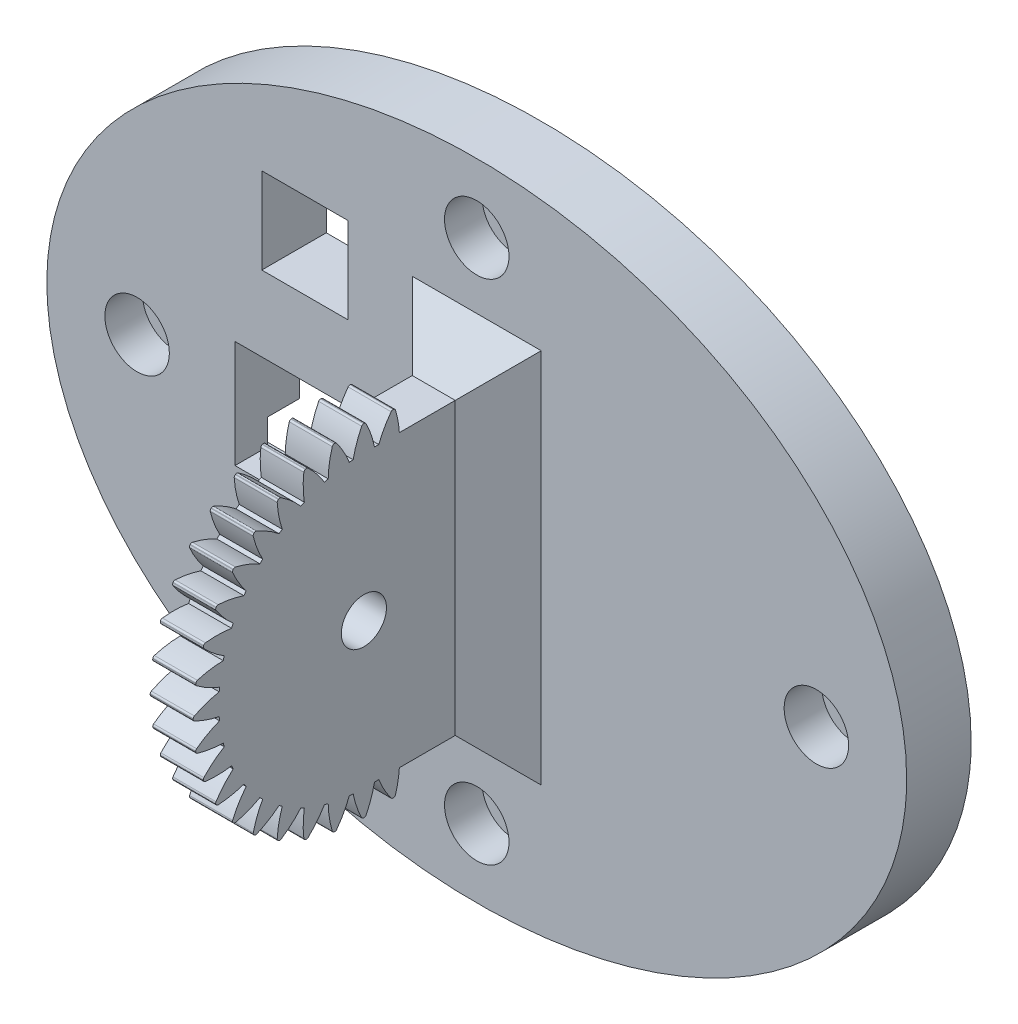
SolidWorks part; units mm, degrees
material "PET"
ref_plane "Front Plane" through (0, 0, 0) normal (0, 0, 1) x (1, 0, 0)
ref_plane "Top Plane" through (0, 0, 0) normal (0, 1, 0) x (1, 0, 0)
ref_plane "Right Plane" through (0, 0, 0) normal (1, 0, 0) x (0, 0, -1)
sketch "Sketch2" plane through (0, 0, 0) normal (0, 0, 1) x (1, 0, 0)
  ellipse E0 centre (0, 0) end of major axis (50.8, 0) minor radius 38.1
  dimension "D1" = 101.6
  dimension "D2" = 76.2
extrude "Boss-Extrude1" add sketch "Sketch2" along normal blind 7.62
ref_plane "Plane1" through (0, 0, 12.7) normal (0, 0, 1) x (1, 0, 0)
sketch "Sketch6" plane through (0, 0, 7.62) normal (0, 0, 1) x (1, 0, 0)
  line L0 (0, 38.1) -> (0, 29.972) construction
  circle A0 centre (0, 29.972) radius 2.2225
  ellipse E0 centre (0, 0) end of major axis (50.8, 0) minor radius 38.1 construction
  ellipse E1 centre (0, 0) end of major axis (50.8, 0) minor radius 38.1
  dimension "D2" = 4.445
  dimension "D1" = 8.128
extrude "Cut-Extrude1" cut sketch "Sketch6" against normal through all
sketch "Sketch7" plane through (0, 0, 7.62) normal (0, 0, 1) x (1, 0, 0)
  circle A0 centre (0, 29.972) radius 3.81
  dimension "D1" = 7.62
extrude "Cut-Extrude2" cut sketch "Sketch7" against normal blind 4.445
mirror "Mirror1" about plane through (0, 0, 0) normal (0, 1, 0) of "Cut-Extrude2", "Cut-Extrude1"
sketch "Sketch8" plane through (0, 0, 7.62) normal (0, 0, 1) x (1, 0, 0)
  line L0 (-50.8, 0) -> (-40.132, 0) construction
  circle A0 centre (-40.132, 0) radius 2.2225
  ellipse E0 centre (0, 0) end of major axis (50.8, 0) minor radius 38.1 construction
  dimension "D2" = 4.445
  dimension "D1" = 10.668
extrude "Cut-Extrude3" cut sketch "Sketch8" against normal through all
sketch "Sketch9" plane through (0, 0, 7.62) normal (0, 0, 1) x (1, 0, 0)
  circle A0 centre (-40.132, 0) radius 3.81
  dimension "D1" = 7.62
extrude "Cut-Extrude4" cut sketch "Sketch9" against normal blind 4.445
mirror "Mirror2" about plane through (0, 0, 0) normal (1, 0, 0) of "Cut-Extrude4", "Cut-Extrude3"
sketch "Sketch10" plane through (0, 0, 7.62) normal (0, 0, 1) x (1, 0, 0)
  line L0 (-36.322, 0) -> (36.322, 0)
  line L2 (-2.54, 17.145) -> (2.54, 17.145)
  line L3 (-2.54, 17.145) -> (-2.54, -17.145)
  line L4 (-2.54, -17.145) -> (2.54, -17.145)
  line L5 (2.54, 17.145) -> (2.54, -17.145)
  line L6 (-2.54, 17.145) -> (2.54, -17.145) construction
  line L7 (-2.54, -17.145) -> (2.54, 17.145) construction
  circle A0 centre (40.132, 0) radius 3.81 construction
  point P4 (0, 0)
  point P12 (0, 0)
  dimension "D1" = 5.08
  dimension "D3" = 34.29
extrude "Boss-Extrude2" add sketch "Sketch10" along normal blind 15.875
chamfer "Chamfer1" distance 5.08 angle 45 4 edges at (2.54, 0, 7.62) (-2.54, 0, 7.62) (0, -17.145, 7.62) (0, 17.145, 7.62)
sketch "Sketch11" plane through (-2.54, 0, 0) normal (-1, 0, 0) x (0, 0, 1)
  line L0 (23.495, 17.145) -> (23.495, -17.145) construction
  circle A0 centre (23.495, 0) radius 2.667
  point P0 (40.005, 0)
  point P6 (0, 0)
  point P7 (37.361, 0)
  dimension "D2" = 5.334
extrude "Cut-Extrude5" cut sketch "Sketch11" against normal through all
sketch "Sketch14" plane through (-2.54, 0, 0) normal (-1, 0, 0) x (0, 0, 1)
  circle A0 centre (23.495, 0) radius 17.145
  circle A1 centre (23.495, 0) radius 2.667
  circle A2 centre (23.495, 0) radius 2.667 construction
  dimension "D1" = 34.29
extrude "Boss-Extrude3" add sketch "Sketch14" against normal up to surface (5.08 mm away) up to face at (2.54, 0, 19.4522)
sketch "Sketch13" plane through (-2.54, 0, 0) normal (-1, 0, 0) x (0, 0, 1)
  line L0 (24.13, 0) -> (33.02, 0) construction
  line L2 (43.6626, 0.0351) -> (43.6626, -0.0351)
  arc A2 (40.5674, 1.27) -> (43.5227, 0.262) centre (38.3898, -9.9507) cw
  arc A3 (40.5674, -1.27) -> (43.5227, -0.262) centre (38.3898, 9.9507) ccw
  arc A6 (23.495, -17.1196) -> (23.495, 17.1196) centre (23.495, 0) ccw
  arc A7 (40.5674, -1.27) -> (40.5674, 1.27) centre (23.495, 0) ccw
  arc A8 (43.5227, -0.262) -> (43.6626, -0.0351) centre (43.4086, -0.0351) ccw
  arc A9 (43.6626, 0.0351) -> (43.5227, 0.262) centre (43.4086, 0.0351) ccw
  point P2 (60.1726, 0.3175)
  point P4 (43.6626, -0.1905)
  point P5 (60.1726, -0.3128)
  point P8 (60.1726, 0.3175)
  point P10 (40.6146, 0)
  point P12 (43.6626, 0.1905)
  point P18 (60.1726, -0.3175)
  point P19 (43.6626, 0)
  point P21 (60.1726, 0.3128)
  point P23 (43.6626, -0.1905)
  point P26 (43.6626, 0.1905)
  dimension "D1" = 0.0254
  dimension "D2" = 11.43
  dimension "D6" = 0.254
  dimension "D3" = 3.048
  dimension "D4" = 1.27
  dimension "D5" = 0.1905
extrude "Boss-Extrude4" add sketch "Sketch13" against normal up to surface (5.08 mm away) up to face at (2.54, 0, 22.3837)
pattern_circular "CirPattern1" count 36 over 360 about axis through (0, 0, 23.495) along (1, 0, 0) of "Boss-Extrude4"
sketch "Sketch16" plane through (0, 0, 7.62) normal (0, 0, 1) x (1, 0, 0)
  line L0 (-50.8, 0) -> (50.8, 0) construction
  line L1 (-50.7718, -1.27) -> (50.7718, -1.27) construction
  line L2 (0, 38.1) -> (0, -38.1) construction
  line L3 (-21.8948, 5.08) -> (-21.8948, -7.62) construction
  line L4 (-28.5623, 5.08) -> (-15.2273, 5.08)
  line L5 (-28.5623, 5.08) -> (-28.5623, -7.62)
  line L6 (-28.5623, -7.62) -> (-15.2273, -7.62)
  line L7 (-15.2273, 5.08) -> (-15.2273, -7.62)
  line L8 (2.5273, 4.8895) -> (13.3223, 4.8895) construction
  line L9 (2.5273, 4.8895) -> (2.5273, -7.4295) construction
  line L10 (2.5273, -7.4295) -> (13.3223, -7.4295) construction
  line L11 (13.3223, 4.8895) -> (13.3223, -7.4295) construction
  line L12 (7.9248, 4.8895) -> (7.9248, -7.4295) construction
  line L13 (-15.2273, 1.27) -> (2.5273, 1.27) construction
  line L14 (-6.35, 1.27) -> (-6.35, 0) construction
  ellipse E0 centre (0, 0) end of major axis (50.8, 0) minor radius 38.1 construction
  point P25 (-28.5623, -1.27)
  point P26 (13.3223, -1.27)
  dimension "D1" = 1.27
  dimension "D2" = 13.335
  dimension "D3" = 12.7
  dimension "D4" = 10.795
  dimension "D5" = 17.7546
  dimension "D6" = 1.27
  dimension "D7" = 6.35
  dimension "D8" = 17.7546
  dimension "D9" = 12.319
extrude "Cut-Extrude7" cut sketch "Sketch16" against normal blind 7.62
sketch "Sketch17" plane through (0, 0, 0) normal (0, 0, -1) x (-1, 0, 0)
  line L0 (0, 0) -> (0, 27.7495) construction
  line L8 (-18.4277, -10.922) -> (39.9923, -10.922)
  line L9 (-18.4277, -10.922) -> (-18.4277, -4.572)
  line L10 (-18.4277, -4.572) -> (39.9923, -4.572)
  line L11 (39.9923, -10.922) -> (39.9923, -4.572)
  line L12 (10.7823, -4.572) -> (10.7823, -10.922) construction
  line L13 (28.5623, 5.08) -> (28.5623, -7.62) construction
  line L14 (28.5623, -7.62) -> (15.2273, -7.62) construction
  circle A0 centre (0, 29.972) radius 2.2225 construction
  dimension "D1" = 11.43
  dimension "D2" = 3.048
  dimension "D4" = 58.42
  dimension "D5" = 6.35
extrude "Cut-Extrude8" cut sketch "Sketch17" against normal blind 3.81
sketch "Sketch19" plane through (0, 0, 0) normal (0, 0, -1) x (-1, 0, 0)
  line L0 (15.2273, 5.08) -> (-50.3464, 5.08) construction
  line L1 (15.2273, -4.572) -> (15.2273, 5.08) construction
  line L2 (-13.2969, 5.08) -> (-2.5019, 5.08)
  line L3 (-13.2969, 5.08) -> (-13.2969, -7.62)
  line L4 (-13.2969, -7.62) -> (-2.5019, -7.62)
  line L5 (-2.5019, 5.08) -> (-2.5019, -7.62)
  ellipse E0 centre (0, 0) end of major axis (-50.8, 0) minor radius 38.1 construction
  dimension "D1" = 10.795
  dimension "D2" = 12.7
  dimension "D3" = 17.7292
extrude "Cut-Extrude9" cut sketch "Sketch19" against normal blind 5.842
sketch "Sketch21" plane through (0, 0, 7.62) normal (0, 0, 1) x (1, 0, 0)
  line L0 (-20.32, 24.13) -> (-20.32, 13.97) construction
  line L1 (-25.4, 24.13) -> (-15.24, 24.13)
  line L2 (-25.4, 24.13) -> (-25.4, 13.97)
  line L3 (-25.4, 13.97) -> (-15.24, 13.97)
  line L4 (-15.24, 24.13) -> (-15.24, 13.97)
  line L5 (-25.4, 19.05) -> (-15.24, 19.05) construction
  point P9 (-20.32, 19.05)
  dimension "D1" = 10.16
  dimension "D2" = 10.16
  dimension "D3" = 20.32
  dimension "D4" = 19.05
extrude "Cut-Extrude11" cut sketch "Sketch21" against normal blind 10.16
sketch "Sketch22" plane through (-2.54, 0, 0) normal (-1, 0, 0) x (0, 0, 1)
  line L0 (12.7, 0) -> (20.828, 0) construction
  line L1 (19.3026, 17.145) -> (12.9526, 17.145)
  line L2 (19.3026, 17.145) -> (19.3026, 19.685)
  line L3 (19.3026, 19.685) -> (12.9526, 19.685)
  line L4 (12.9526, 17.145) -> (12.9526, 19.685)
  line L5 (12.7, 17.145) -> (12.7, -17.145) construction
  line L6 (19.3026, -19.685) -> (12.9526, -19.685)
  line L7 (12.9526, -17.145) -> (12.9526, -19.685)
  line L8 (19.3026, -17.145) -> (12.9526, -17.145)
  line L9 (19.3026, -17.145) -> (19.3026, -19.685)
  circle A0 centre (23.495, 0) radius 2.667 construction
  dimension "D1" = 6.35
  dimension "D2" = 2.54
extrude "Cut-Extrude12" cut sketch "Sketch22" against normal up to surface (5.08 mm away) up to face at (2.54, 0, 30.4085)
equation "\"ft\"=0.24"
